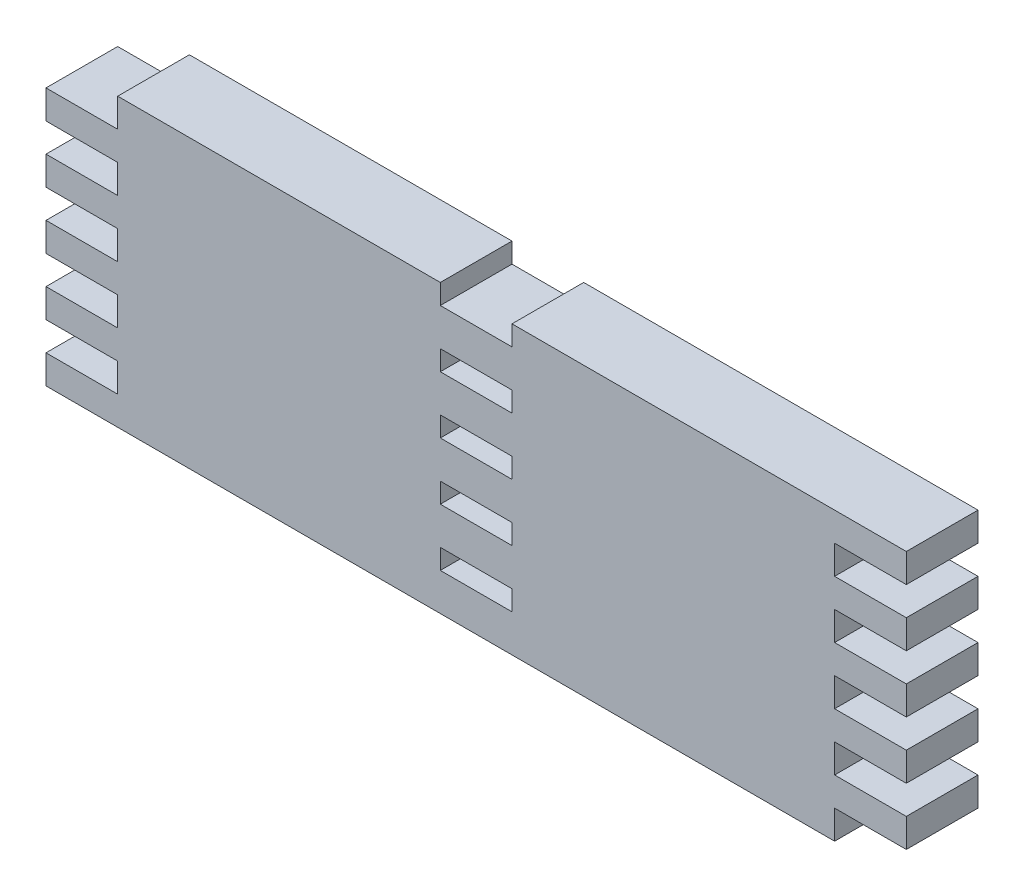
SolidWorks part; units mm, degrees
ref_plane "Front Plane" through (0, 0, 0) normal (0, 0, 1) x (1, 0, 0)
ref_plane "Top Plane" through (0, 0, 0) normal (0, 1, 0) x (1, 0, 0)
ref_plane "Right Plane" through (0, 0, 0) normal (1, 0, 0) x (0, 0, -1)
sketch "Sketch1" plane through (0, 0, 0) normal (0, 0, 1) x (1, 0, 0)
  line L1 (30, -10) -> (-30, -10)
  line L2 (30, -10) -> (30, 10)
  line L3 (30, 10) -> (-30, 10)
  line L4 (-30, -10) -> (-30, 10)
  line L5 (30, -10) -> (-30, 10) construction
  line L6 (30, 10) -> (-30, -10) construction
  point P0 (0, 0)
  dimension "D1" = 20
  dimension "D2" = 60
extrude "Boss-Extrude1" add sketch "Sketch1" along normal mid plane 5
sketch "Sketch2" plane through (0, 0, 2.5) normal (0, 0, 1) x (1, 0, 0)
  line L0 (-30, 6) -> (-25, 6)
  line L1 (-30, 10) -> (-25, 10)
  line L2 (-30, 10) -> (-30, 8)
  line L3 (-30, 8) -> (-25, 8)
  line L4 (-25, 10) -> (-25, 8)
  line L5 (-25, 6) -> (-25, 4)
  line L6 (-30, 4) -> (-25, 4)
  line L7 (-30, 6) -> (-30, 4)
  line L8 (-30, 2) -> (-25, 2)
  line L9 (-25, 2) -> (-25, 0)
  line L10 (-30, 0) -> (-25, 0)
  line L11 (-30, 2) -> (-30, 0)
  line L12 (-30, -2) -> (-25, -2)
  line L13 (-25, -2) -> (-25, -4)
  line L14 (-30, -4) -> (-25, -4)
  line L15 (-30, -2) -> (-30, -4)
  line L16 (-30, -6) -> (-25, -6)
  line L17 (-25, -6) -> (-25, -8)
  line L18 (-30, -8) -> (-25, -8)
  line L19 (-30, -6) -> (-30, -8)
  dimension "D1" = 5
  dimension "D2" = 2
  dimension "D3" = 5
extrude "Cut-Extrude1" cut sketch "Sketch2" against normal through all
sketch "Sketch3" plane through (0, 0, 2.5) normal (0, 0, 1) x (1, 0, 0)
  line L0 (-30, 8) -> (-25, 8) construction
  line L1 (30, -10) -> (25, -10)
  line L2 (30, -10) -> (30, -8)
  line L3 (30, -8) -> (25, -8)
  line L4 (25, -10) -> (25, -8)
  line L5 (-30, -8) -> (-30, -10) construction
  line L6 (25, -6) -> (25, -4)
  line L7 (30, -4) -> (25, -4)
  line L8 (30, -6) -> (30, -4)
  line L9 (30, -6) -> (25, -6)
  line L10 (25, -2) -> (25, 0)
  line L11 (30, 0) -> (25, 0)
  line L12 (30, -2) -> (30, 0)
  line L13 (30, -2) -> (25, -2)
  line L14 (25, 2) -> (25, 4)
  line L15 (30, 4) -> (25, 4)
  line L16 (30, 2) -> (30, 4)
  line L17 (30, 2) -> (25, 2)
  line L18 (25, 6) -> (25, 8)
  line L19 (30, 8) -> (25, 8)
  line L20 (30, 6) -> (30, 8)
  line L21 (30, 6) -> (25, 6)
  dimension "D1" = 5
extrude "Cut-Extrude2" cut sketch "Sketch3" against normal blind 5
sketch "Sketch4" plane through (0, 0, 2.5) normal (0, 0, 1) x (1, 0, 0)
  line L0 (30, 10) -> (-25, 10) construction
  line L1 (-2.5, 10) -> (2.5, 10)
  line L2 (-2.5, 10) -> (-2.5, 8.6057)
  line L3 (-2.5, 8.6057) -> (2.5, 8.6057)
  line L4 (2.5, 10) -> (2.5, 8.6057)
  line L5 (0, 8.6057) -> (0, 0) construction
  line L6 (-2.5, 6) -> (-2.5, 4.6057)
  line L7 (-2.5, 6) -> (2.5, 6)
  line L8 (-2.5, 4.6057) -> (2.5, 4.6057)
  line L9 (2.5, 6) -> (2.5, 4.6057)
  line L10 (-2.5, 2) -> (-2.5, 0.6057)
  line L11 (-2.5, 2) -> (2.5, 2)
  line L12 (-2.5, 0.6057) -> (2.5, 0.6057)
  line L13 (2.5, 2) -> (2.5, 0.6057)
  line L14 (-2.5, -2) -> (-2.5, -3.3943)
  line L15 (-2.5, -2) -> (2.5, -2)
  line L16 (-2.5, -3.3943) -> (2.5, -3.3943)
  line L17 (2.5, -2) -> (2.5, -3.3943)
  line L18 (-2.5, -6) -> (-2.5, -7.3943)
  line L19 (-2.5, -6) -> (2.5, -6)
  line L20 (-2.5, -7.3943) -> (2.5, -7.3943)
  line L21 (2.5, -6) -> (2.5, -7.3943)
  dimension "D1" = 1.3943
  dimension "D2" = 5
  dimension "D3" = 5
extrude "Cut-Extrude3" cut sketch "Sketch4" against normal blind 5
